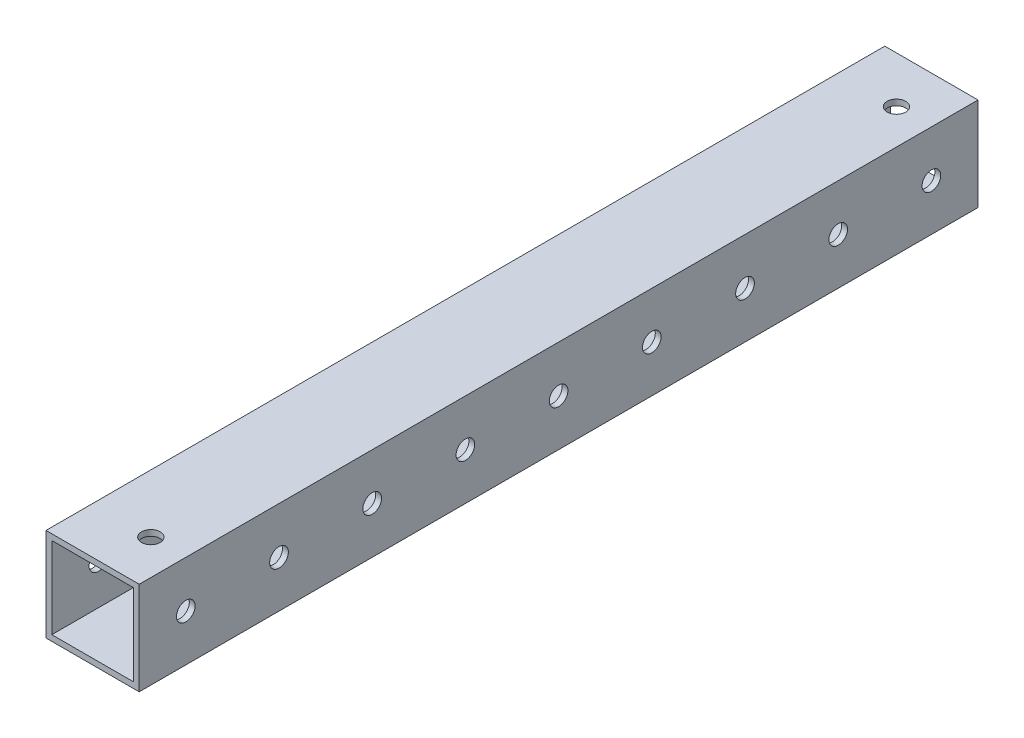
SolidWorks part; units mm, degrees
ref_plane "Front Plane" through (0, 0, 0) normal (0, 0, 1) x (1, 0, 0)
ref_plane "Top Plane" through (0, 0, 0) normal (0, 1, 0) x (1, 0, 0)
ref_plane "Right Plane" through (0, 0, 0) normal (1, 0, 0) x (0, 0, -1)
sketch "Sketch1" plane through (0, 0, 0) normal (0, 0, 1) x (1, 0, 0)
  line L1 (0, 0) -> (25.4, 0)
  line L2 (0, 0) -> (0, 25.4)
  line L3 (0, 25.4) -> (25.4, 25.4)
  line L4 (25.4, 0) -> (25.4, 25.4)
  line L5 (1.5875, 1.5875) -> (23.8125, 1.5875)
  line L6 (1.5875, 1.5875) -> (1.5875, 23.8125)
  line L7 (1.5875, 23.8125) -> (23.8125, 23.8125)
  line L8 (23.8125, 1.5875) -> (23.8125, 23.8125)
  dimension "D1" = 25.4
  dimension "D2" = 1.5875
  dimension "D3" = 1.5875
  dimension "D4" = 1.5875
  dimension "D5" = 1.5875
extrude "Boss-Extrude1" add sketch "Sketch1" along normal blind 228.6
sketch "Sketch3" plane through (0, 25.4, 0) normal (0, 1, 0) x (1, 0, 0)
  line L0 (0, -228.6) -> (0, 0) construction
  line L1 (25.4, -228.6) -> (0, -228.6) construction
  line L2 (25.4, 0) -> (0, 0) construction
  circle A0 centre (15.875, -215.9) radius 2.54
  circle A1 centre (15.875, -12.7) radius 2.54
  dimension "D3" = 5.08
  dimension "D1" = 15.875
  dimension "D2" = 12.7
  dimension "D4" = 12.7
extrude "Cut-Extrude2" cut sketch "Sketch3" against normal through all
sketch "Sketch4" plane through (25.4, 0, 0) normal (1, 0, 0) x (0, 0, -1)
  line L0 (-228.6, 25.4) -> (0, 25.4) construction
  line L1 (-228.6, 0) -> (-228.6, 25.4) construction
  circle A0 centre (-215.9, 12.7) radius 2.54
  circle A2 centre (-190.5, 12.7) radius 2.54
  circle A3 centre (-165.1, 12.7) radius 2.54
  circle A4 centre (-139.7, 12.7) radius 2.54
  circle A5 centre (-114.3, 12.7) radius 2.54
  circle A6 centre (-88.9, 12.7) radius 2.54
  circle A7 centre (-63.5, 12.7) radius 2.54
  circle A8 centre (-38.1, 12.7) radius 2.54
  circle A9 centre (-12.7, 12.7) radius 2.54
  dimension "D1" = 5.08
  dimension "D2" = 12.7
  dimension "D3" = 12.7
  dimension "D4" = 9
extrude "Cut-Extrude3" cut sketch "Sketch4" against normal through all
